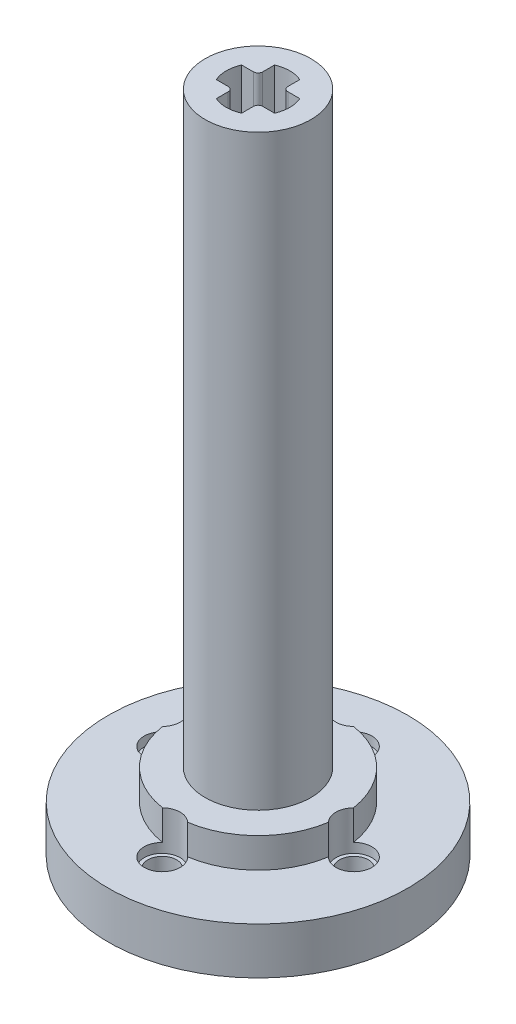
SolidWorks part; units mm, degrees
ref_plane "Front Plane" through (0, 0, 0) normal (0, 0, 1) x (1, 0, 0)
ref_plane "Top Plane" through (0, 0, 0) normal (0, 1, 0) x (1, 0, 0)
ref_plane "Right Plane" through (0, 0, 0) normal (1, 0, 0) x (0, 0, -1)
sketch "Sketch1" plane through (0, 0, 0) normal (0, 0, 1) x (1, 0, 0)
  line L0 (0, 0) -> (0, 55.4)
  line L1 (0, 0) -> (12.5, 0)
  line L2 (12.5, 0) -> (12.5, 3.9)
  line L3 (12.5, 3.9) -> (7, 3.9)
  line L6 (7, 3.9) -> (7, 6.4)
  line L7 (7, 6.4) -> (4.41, 6.4)
  line L8 (4.41, 6.4) -> (4.41, 55.4)
  line L13 (4.41, 55.4) -> (0, 55.4)
  dimension "D1" = 55.4
  dimension "D4" = 2.5
  dimension "D6" = 3.9
  dimension "D7" = 8.82
  dimension "D9" = 7
  dimension "D11" = 12.5
revolve "Revolve1" add sketch "Sketch1" angle 360 about L0
sketch "Sketch2" plane through (0, 55.4, 0) normal (0, 1, 0) x (1, 0, 0)
  line L0 (0.935, -1.435) -> (0.935, -2.35) construction
  line L1 (-0.935, 2.35) -> (0.935, 2.35) construction
  line L2 (-0.935, 2.35) -> (-0.935, 1.435) construction
  line L3 (-0.935, -2.35) -> (0.935, -2.35) construction
  line L4 (0.935, 2.35) -> (0.935, 1.435) construction
  line L5 (0, -2.35) -> (0, 0) construction
  line L6 (0, 0) -> (0, 2.35) construction
  line L7 (-2.35, 0.935) -> (-1.435, 0.935) construction
  line L8 (-2.35, 0.935) -> (-2.35, -0.935) construction
  line L9 (-2.35, -0.935) -> (-1.435, -0.935) construction
  line L10 (2.35, 0.935) -> (2.35, -0.935) construction
  line L11 (0, 0) -> (2.35, 0) construction
  line L12 (-2.35, 0) -> (0, 0) construction
  line L13 (1.435, -0.935) -> (2.35, -0.935) construction
  line L14 (-0.935, -1.435) -> (-0.935, -2.35) construction
  line L15 (1.435, 0.935) -> (2.35, 0.935) construction
  line L16 (-1.055, 2.43) -> (-1.055, 1.435)
  line L17 (-2.43, 1.055) -> (-1.435, 1.055)
  line L18 (-2.43, -1.055) -> (-1.435, -1.055)
  line L19 (-1.055, -1.435) -> (-1.055, -2.43)
  line L20 (1.055, -1.435) -> (1.055, -2.43)
  line L21 (1.435, -1.055) -> (2.43, -1.055)
  line L22 (1.435, 1.055) -> (2.43, 1.055)
  line L23 (1.055, 2.43) -> (1.055, 1.435)
  arc A0 (-0.935, 1.435) -> (-1.435, 0.935) centre (-1.435, 1.435) cw construction
  arc A1 (-1.435, -0.935) -> (-0.935, -1.435) centre (-1.435, -1.435) cw construction
  arc A2 (0.935, -1.435) -> (1.435, -0.935) centre (1.435, -1.435) cw construction
  arc A3 (0.935, 1.435) -> (1.435, 0.935) centre (1.435, 1.435) ccw construction
  arc A4 (2.35, -0.935) -> (2.35, 0.935) centre (0, 0) ccw construction
  arc A5 (0.935, 2.35) -> (-0.935, 2.35) centre (0, 0) ccw construction
  arc A6 (-2.35, 0.935) -> (-2.35, -0.935) centre (0, 0) ccw construction
  arc A7 (-0.935, -2.35) -> (0.935, -2.35) centre (0, 0) ccw construction
  arc A8 (-1.055, 1.435) -> (-1.435, 1.055) centre (-1.435, 1.435) cw
  arc A9 (-2.43, 1.055) -> (-2.43, -1.055) centre (0, 0) ccw
  arc A10 (-1.435, -1.055) -> (-1.055, -1.435) centre (-1.435, -1.435) cw
  arc A11 (-1.055, -2.43) -> (1.055, -2.43) centre (0, 0) ccw
  arc A12 (1.055, -1.435) -> (1.435, -1.055) centre (1.435, -1.435) cw
  arc A13 (2.43, -1.055) -> (2.43, 1.055) centre (0, 0) ccw
  arc A14 (1.055, 1.435) -> (1.435, 1.055) centre (1.435, 1.435) ccw
  arc A15 (1.055, 2.43) -> (-1.055, 2.43) centre (0, 0) ccw
  point P0 (0, 0)
  point P4 (0, 0)
  point P22 (-0.935, -0.935)
  point P27 (0.935, -0.935)
  point P30 (0.935, 0.935)
  dimension "D3" = 0.5
  dimension "D4" = 0.12
  dimension "D1" = 1.87
  dimension "D2" = 2.35
extrude "Cut-Extrude1" cut sketch "Sketch2" against normal up to next contours L14 A7 L0 A2 L13 A4 L15 A3 L4 A5 L2 A0 L7 A6 L9 A1 | L23 A15 L16 A8 L17 A9 L18 A10 L19 A11 L20 A12 L21 A13 L22 A14
sketch "Sketch3" plane through (0, 3.9, 0) normal (0, 1, 0) x (1, 0, 0)
  line L0 (0, 0) -> (0, 8) construction
  line L2 (0, 0) -> (-8, 0) construction
  circle A0 centre (0, 8) radius 1.5
  circle A2 centre (0, -8) radius 1.5
  circle A3 centre (-8, 0) radius 1.5
  circle A4 centre (8, 0) radius 1.5
  point P10 (0, 0)
  dimension "D1" = 8
  dimension "D2" = 3
extrude "Cut-Extrude2" cut sketch "Sketch3" against normal blind 0.7937 and the other way up to surface other way up to face at (0, 6.4, -4.41)
sketch "Sketch5" plane through (0, 3.9, 0) normal (0, 1, 0) x (1, 0, 0)
  circle A0 centre (8, 0) radius 1.2
  circle A1 centre (0, 8) radius 1.2
  circle A2 centre (-8, 0) radius 1.2
  circle A3 centre (0, -8) radius 1.2
  dimension "D1" = 2.4
extrude "Cut-Extrude3" cut sketch "Sketch5" against normal up to next
